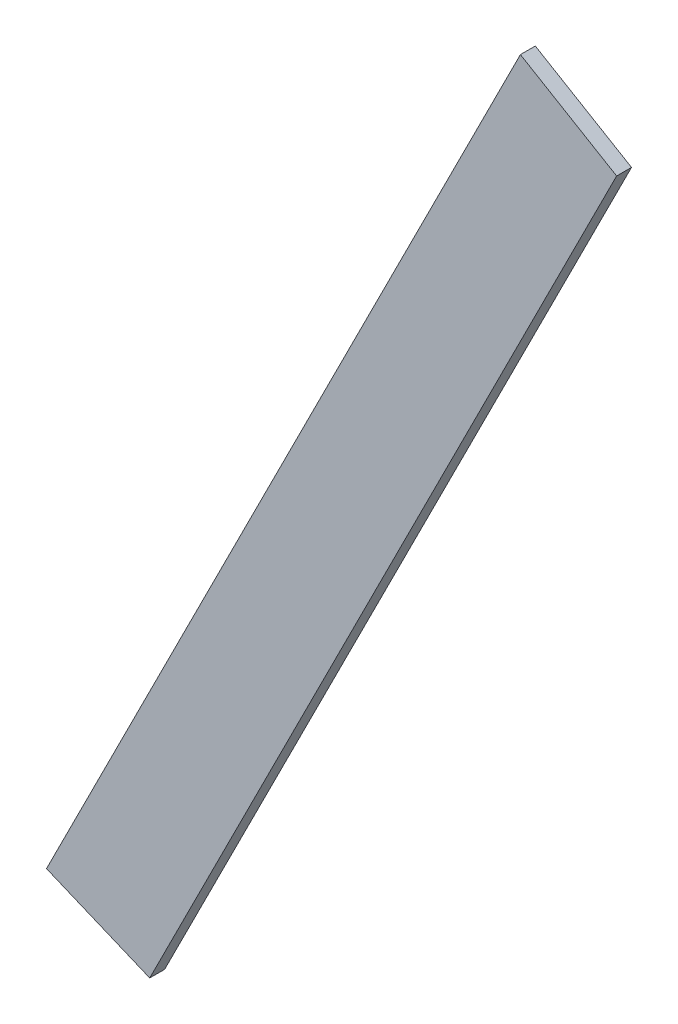
SolidWorks part; units mm, degrees
ref_plane "Front Plane" through (0, 0, 0) normal (0, 0, 1) x (1, 0, 0)
ref_plane "Top Plane" through (0, 0, 0) normal (0, 1, 0) x (1, 0, 0)
ref_plane "Right Plane" through (0, 0, 0) normal (1, 0, 0) x (0, 0, -1)
sketch "Sketch1" plane through (0, 0, 0) normal (0, 0, 1) x (1, 0, 0)
  line L0 (31.4176, -12.7757) -> (17.5407, -6.9826)
  line L2 (17.5407, -6.9826) -> (81.2521, 119.6468)
  line L4 (31.4176, -12.7757) -> (94.1861, 111.9797)
  line L5 (94.1861, 111.9797) -> (81.2521, 119.6468)
  line L6 (153.026, 77.1004) -> (-19.0179, 179.0851) construction
  line L7 (-89.9119, 37.8749) -> (94.6513, -39.1734) construction
  dimension "D1" = 15
extrude "Boss-Extrude1" add sketch "Sketch1" along normal blind 2
ref_plane "Plane1" through (23.5006, -11.8239, 0) normal (0.8933, -0.4495, 0) x (0, 0, -1)
